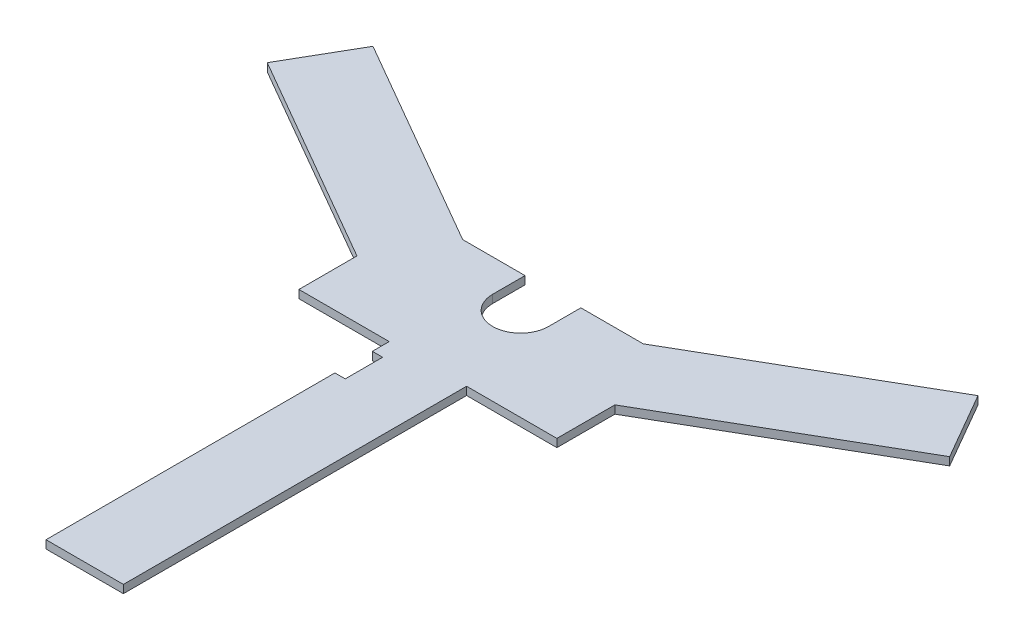
SolidWorks part; units mm, degrees
ref_plane "Front Plane" through (0, 0, 0) normal (0, 0, 1) x (1, 0, 0)
ref_plane "Top Plane" through (0, 0, 0) normal (0, 1, 0) x (1, 0, 0)
ref_plane "Right Plane" through (0, 0, 0) normal (1, 0, 0) x (0, 0, -1)
sketch "Sketch1" plane through (0, 0, 0) normal (0, 1, 0) x (1, 0, 0)
  line L0 (0, 11.43) -> (7.62, 24.6282)
  line L1 (0, 0) -> (50.8, 0)
  line L2 (0, 0) -> (0, 11.43)
  line L3 (0, 11.43) -> (50.8, 11.43)
  line L4 (50.8, 0) -> (50.8, 11.43)
  line L5 (50.8, 11.43) -> (43.18, 24.6282)
  line L6 (7.62, 24.6282) -> (43.18, 24.6282)
  line L7 (3.81, 18.0291) -> (44.3832, -5.3958) construction
  line L8 (17.78, 0) -> (33.02, 0)
  line L9 (17.78, 0) -> (17.78, -19.3279)
  line L10 (17.78, -19.3279) -> (33.02, -19.3279)
  line L11 (33.02, 0) -> (33.02, -19.3279)
  line L12 (46.99, 18.0291) -> (8.5613, -4.1577) construction
  line L13 (25.4, -19.3279) -> (25.4, 20.0669) construction
  line L14 (43.18, 24.6282) -> (50.8, 11.43)
  line L15 (19.9, 18.2641) -> (30.9, 18.2641)
  line L16 (19.9, 18.2641) -> (19.9, 24.6282)
  line L17 (19.9, 24.6282) -> (30.9, 24.6282)
  line L18 (30.9, 18.2641) -> (30.9, 24.6282)
  line L19 (17.78, -19.3279) -> (33.02, -19.3279)
  line L20 (17.78, -19.3279) -> (17.78, -67.5879)
  line L21 (17.78, -67.5879) -> (33.02, -67.5879)
  line L22 (33.02, -19.3279) -> (33.02, -67.5879)
  line L23 (43.18, 24.6282) -> (84.9744, 48.7582)
  line L24 (50.8, 11.43) -> (92.5944, 35.56)
  line L25 (84.9744, 48.7582) -> (92.5944, 35.56)
  line L26 (0, 11.43) -> (7.62, 24.6282)
  line L27 (0, 11.43) -> (-41.7944, 35.56)
  line L28 (7.62, 24.6282) -> (-34.1744, 48.7582)
  line L29 (-41.7944, 35.56) -> (-34.1744, 48.7582)
  circle A9 centre (25.4, 18.2641) radius 5.5
  point P23 (25.4, 5.5641)
  dimension "D28" = 12.7
  dimension "D29" = 11
  dimension "D1" = 50.8
  dimension "D2" = 11.43
  dimension "D3" = 30
  dimension "D4" = 15.24
  dimension "D5" = 30
  dimension "D6" = 15.24
  dimension "D7" = 15.24
  dimension "D8" = 24.892
  dimension "D9" = 17.78
  dimension "D30" = 48.26
  dimension "D31" = 48.26
  dimension "D32" = 48.26
extrude "Boss-Extrude2" add sketch "Sketch1" along normal blind 1.5875
sketch "Sketch6" plane through (0, 0, 0) normal (0, -1, 0) x (-1, 0, 0)
  line L0 (-17.78, 0) -> (-17.78, -67.5879) construction
  line L1 (-17.78, -10.6919) -> (-19.812, -10.6919)
  line L2 (-17.78, -10.6919) -> (-17.78, -3.3259)
  line L3 (-17.78, -3.3259) -> (-19.812, -3.3259)
  line L4 (-19.812, -10.6919) -> (-19.812, -3.3259)
  line L6 (0, 0) -> (-17.78, 0) construction
  dimension "D3" = 2.032
  dimension "D4" = 3.3259
  dimension "D5" = 10.6919
extrude "Cut-Extrude4" cut sketch "Sketch6" against normal blind 2.54
sketch "Sketch7" plane through (0, 0, 0) normal (0, -1, 0) x (-1, 0, 0)
  line L0 (-17.78, -67.5879) -> (-33.02, -67.5879) construction
  line L1 (-33.02, 0) -> (-33.02, -67.5879) construction
  line L2 (-43.18, 24.6282) -> (-84.9744, 48.7582) construction
  line L3 (-84.9744, 48.7582) -> (-92.5944, 35.56) construction
  line L4 (41.7944, 35.56) -> (34.1744, 48.7582) construction
  line L5 (-7.62, 24.6282) -> (34.1744, 48.7582) construction
  line L6 (0, 11.43) -> (41.7944, 35.56) construction
  circle A0 centre (-25.4, -59.9679) radius 1
  circle A1 centre (-25.4, -47.2679) radius 1
  circle A2 centre (-71.1867, 31.9991) radius 1
  circle A3 centre (-82.1853, 38.3491) radius 1
  circle A4 centre (31.3853, 38.3491) radius 1
  circle A5 centre (20.3867, 31.9991) radius 1
  dimension "D3" = 2
  dimension "D4" = 2
  dimension "D5" = 7.62
  dimension "D6" = 7.62
  dimension "D7" = 7.62
  dimension "D8" = 7.62
  dimension "D9" = 7.62
  dimension "D10" = 20.32
  dimension "D11" = 2
  dimension "D12" = 2
  dimension "D13" = 7.62
  dimension "D14" = 20.32
  dimension "D15" = 7.62
  dimension "D16" = 2
  dimension "D17" = 2
  dimension "D18" = 7.62
  dimension "D1" = 7.62
  dimension "D2" = 20.32
